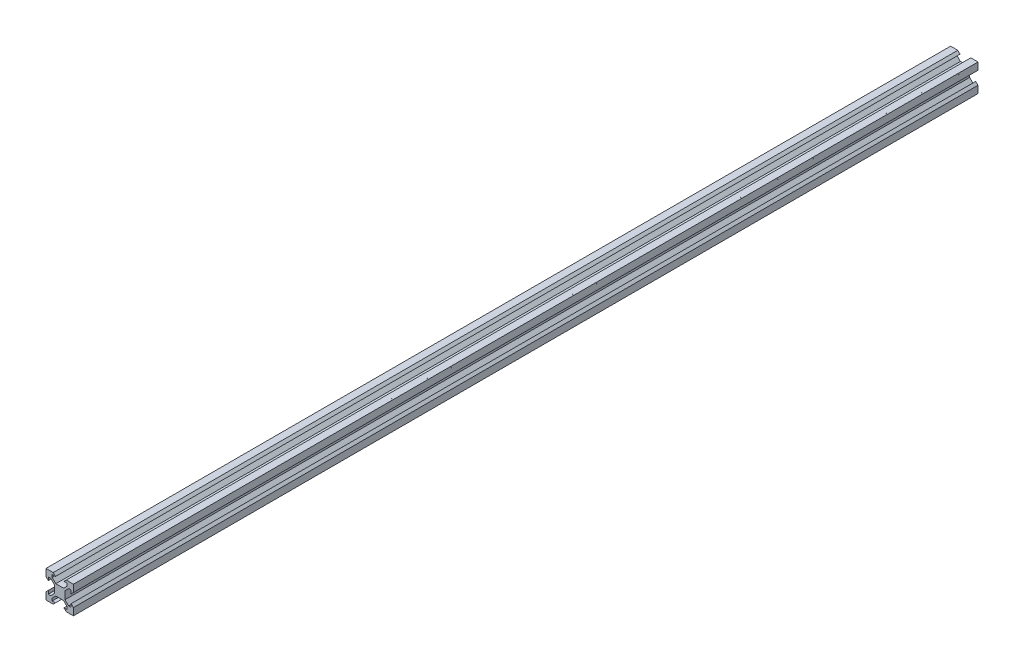
SolidWorks part; units mm, degrees
ref_plane "Front Plane" through (0, 0, 0) normal (0, 0, 1) x (1, 0, 0)
ref_plane "Top Plane" through (0, 0, 0) normal (0, 1, 0) x (1, 0, 0)
ref_plane "Right Plane" through (0, 0, 0) normal (1, 0, 0) x (0, 0, -1)
sketch "Sketch1" plane through (0, 0, 0) normal (0, 0, 1) x (1, 0, 0)
  line L88 (2.8343, 3.894) -> (-2.8343, 3.894)
  line L89 (-2.8343, 3.894) -> (-5.5, 6.5588)
  line L90 (-5.5, 6.5588) -> (-5.5, 8.3491)
  line L91 (-5.5, 8.3491) -> (-3.1, 8.3491)
  line L92 (-3.1, 8.3491) -> (-4.75, 9.9986)
  line L93 (-4.75, 9.9986) -> (-10, 9.9986)
  line L94 (-10, 9.9986) -> (-10, 4.747)
  line L95 (-10, 4.747) -> (-8.35, 3.0975)
  line L96 (-8.35, 3.0975) -> (-8.3507, 5.4975)
  line L97 (-8.3507, 5.4975) -> (-6.5605, 5.498)
  line L98 (-6.5605, 5.498) -> (-3.8948, 2.8332)
  line L99 (-3.8948, 2.8332) -> (-3.8948, -2.8332)
  line L100 (-3.8948, -2.8332) -> (-6.5605, -5.498)
  line L101 (-6.5605, -5.498) -> (-8.3507, -5.4975)
  line L102 (-8.3507, -5.4975) -> (-8.35, -3.0975)
  line L103 (-8.35, -3.0975) -> (-10, -4.747)
  line L104 (-10, -4.747) -> (-10, -9.9986)
  line L105 (-10, -9.9986) -> (-4.75, -9.9986)
  line L106 (-4.75, -9.9986) -> (-3.1, -8.3491)
  line L107 (-3.1, -8.3491) -> (-5.5, -8.3491)
  line L108 (-5.5, -8.3491) -> (-5.5, -6.5588)
  line L109 (-5.5, -6.5588) -> (-2.8343, -3.894)
  line L110 (-2.8343, -3.894) -> (2.8343, -3.894)
  line L111 (2.8343, -3.894) -> (5.5, -6.5588)
  line L112 (5.5, -6.5588) -> (5.5, -8.3491)
  line L113 (5.5, -8.3491) -> (3.1, -8.3491)
  line L114 (3.1, -8.3491) -> (4.75, -9.9986)
  line L115 (4.75, -9.9986) -> (10, -9.9986)
  line L116 (10, -9.9986) -> (10, -4.747)
  line L117 (10, -4.747) -> (8.35, -3.0975)
  line L118 (8.35, -3.0975) -> (8.3507, -5.4975)
  line L119 (8.3507, -5.4975) -> (6.5605, -5.498)
  line L120 (6.5605, -5.498) -> (3.8948, -2.8332)
  line L121 (3.8948, -2.8332) -> (3.8948, 2.8332)
  line L122 (3.8948, 2.8332) -> (6.5605, 5.498)
  line L123 (6.5605, 5.498) -> (8.3507, 5.4975)
  line L124 (8.3507, 5.4975) -> (8.35, 3.0975)
  line L125 (8.35, 3.0975) -> (10, 4.747)
  line L126 (10, 4.747) -> (10, 9.9986)
  line L127 (10, 9.9986) -> (4.75, 9.9986)
  line L128 (4.75, 9.9986) -> (3.1, 8.3491)
  line L129 (3.1, 8.3491) -> (5.5, 8.3491)
  line L130 (5.5, 8.3491) -> (5.5, 6.5588)
  line L131 (5.5, 6.5588) -> (2.8343, 3.894)
  dimension "D2" = 5.25
  dimension "D3" = 19.9971
  dimension "D4" = 20
extrude "Boss-Extrude1" add sketch "Sketch1" along normal blind 660
